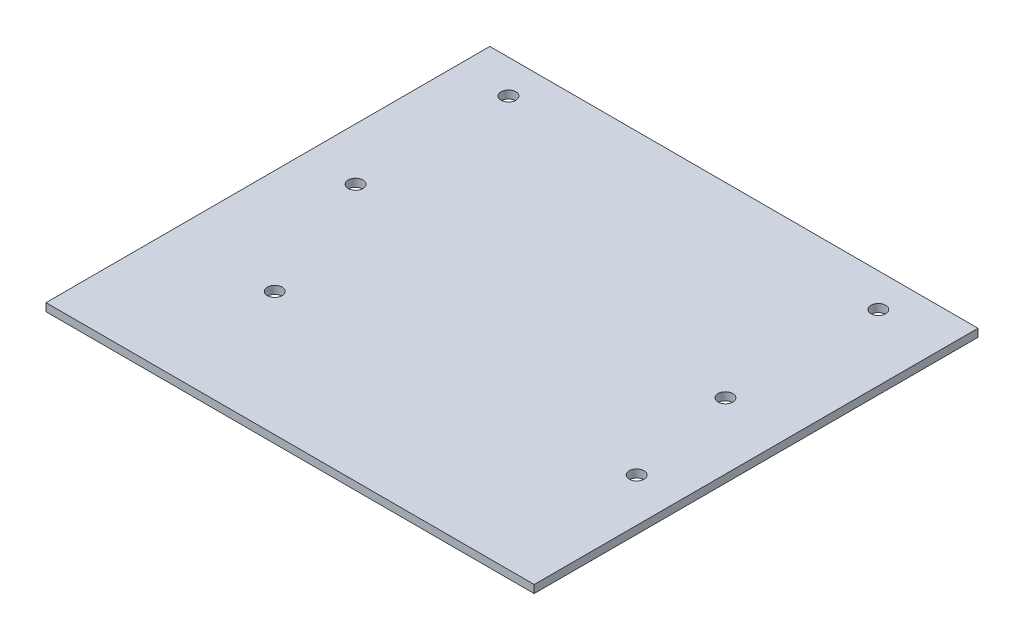
SolidWorks part; units mm, degrees
ref_plane "Спереди" through (0, 0, 0) normal (0, 0, 1) x (1, 0, 0)
ref_plane "Сверху" through (0, 0, 0) normal (0, 1, 0) x (1, 0, 0)
ref_plane "Справа" through (0, 0, 0) normal (1, 0, 0) x (0, 0, -1)
sketch "Эскиз1" plane through (0, 0, 0) normal (0, 1, 0) x (1, 0, 0)
  line L0 (10.5996, 83.1802) -> (85.5996, 83.1802) construction
  line L1 (0, 0) -> (99, 0)
  line L2 (0, 0) -> (0, 90)
  line L3 (0, 90) -> (99, 90)
  line L4 (99, 0) -> (99, 90)
  line L5 (85.5996, 83.1802) -> (85.5996, 52.1802) construction
  line L6 (85.5996, 52.1802) -> (10.5996, 52.1802) construction
  line L7 (10.5996, 52.1802) -> (10.5996, 83.1802) construction
  line L8 (85.5996, 83.1802) -> (99, 90) construction
  line L9 (0, 90) -> (10.5996, 83.1802) construction
  line L10 (85.5996, 52.1802) -> (90.1538, 29.6223) construction
  line L11 (90.1538, 29.6223) -> (99, 0) construction
  line L12 (10.5996, 52.1802) -> (21.2195, 25.17) construction
  line L13 (21.2195, 25.17) -> (0, 0) construction
  circle A0 centre (10.5996, 83.1802) radius 1.5
  circle A1 centre (85.5996, 83.1802) radius 1.5
  circle A2 centre (10.5996, 52.1802) radius 1.5
  circle A3 centre (85.5996, 52.1802) radius 1.5
  circle A4 centre (21.2195, 25.17) radius 1.5
  circle A5 centre (90.1538, 29.6223) radius 1.5
  dimension "D7" = 3
  dimension "D1" = 99
  dimension "D2" = 90
  dimension "D3" = 75
  dimension "D4" = 31
  dimension "D5" = 12.604
  dimension "D6" = 15.036
  dimension "D8" = 29.023
  dimension "D9" = 32.921
  dimension "D10" = 23.013
  dimension "D11" = 30.915
extrude "Бобышка-Вытянуть1" add sketch "Эскиз1" along normal blind 1.6
